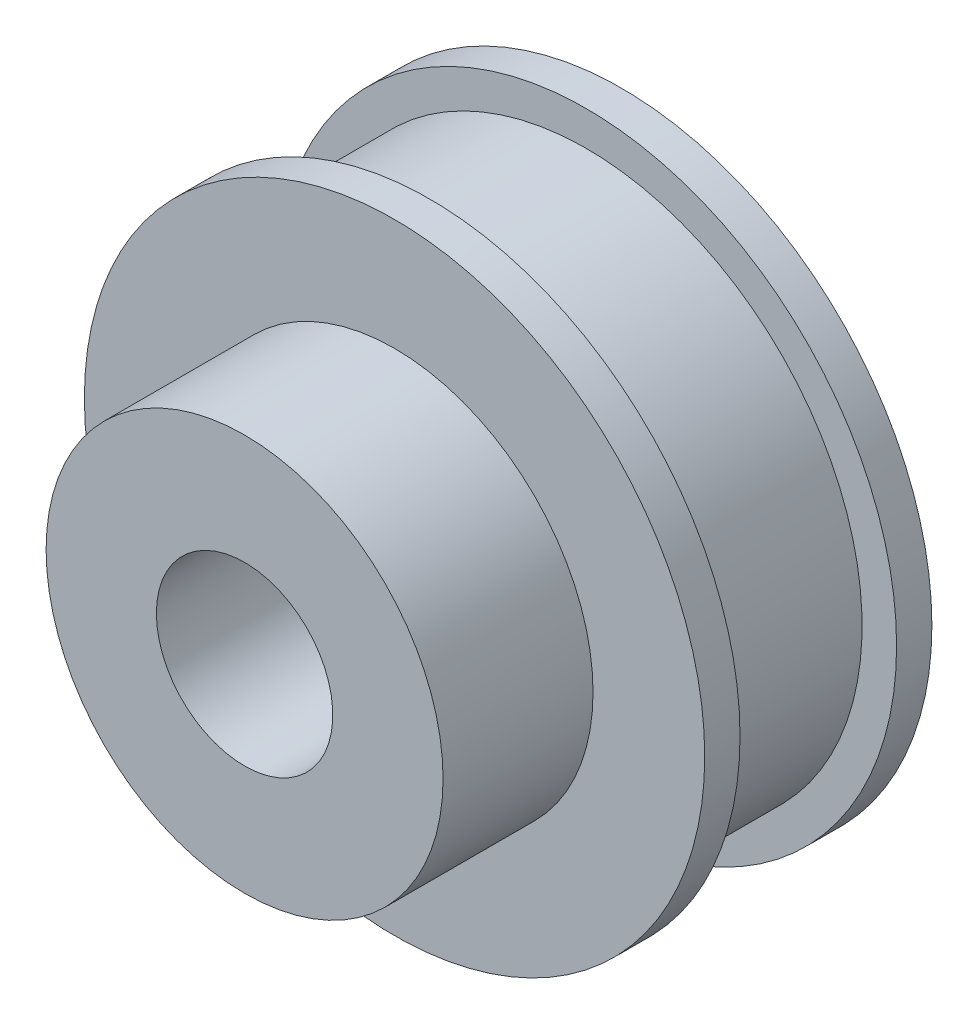
SolidWorks part; units mm, degrees
ref_plane "Front Plane" through (0, 0, 0) normal (1, 0, 0) x (0, 1, 0)
ref_plane "Top Plane" through (0, 0, 0) normal (0, 0, 1) x (0, 1, 0)
ref_plane "Right Plane" through (0, 0, 0) normal (0, 1, 0) x (-1, 0, 0)
sketch "Sketch1" plane through (0, 0, 0) normal (0, 1, 0) x (-1, 0, 0)
  line L0 (0, 0) -> (-14.065, 0) construction
  line L1 (-14.065, 0.8) -> (-14.065, -0.8)
  line L2 (-14.065, 0.8) -> (-12.5, 0.8)
  line L3 (-12.5, 0.8) -> (-12.5, 7.9)
  line L4 (-12.5, 7.9) -> (-14.065, 7.9)
  line L5 (-14.065, 7.9) -> (-14.065, 9.5)
  line L6 (-14.065, 9.5) -> (-9, 9.5)
  line L7 (-9, 9.5) -> (-9, 16.3)
  line L8 (-9, 16.3) -> (-4, 16.3)
  line L9 (-4, 16.3) -> (-4, -0.8)
  line L10 (-4, -0.8) -> (-14.065, -0.8)
  line L11 (0, 0) -> (0, 9.4649) construction
  line L12 (-4, 7.0088) -> (-12.5, 7.0088) construction
  point P6 (-14.065, 0)
  dimension "D1" = 14.065
  dimension "D2" = 5
  dimension "D3" = 10.065
  dimension "D4" = 17.1
  dimension "D5" = 7.1
  dimension "D6" = 6.8
  dimension "D7" = 8.5
revolve "Revolve1" add sketch "Sketch1" angle 360 about L11
